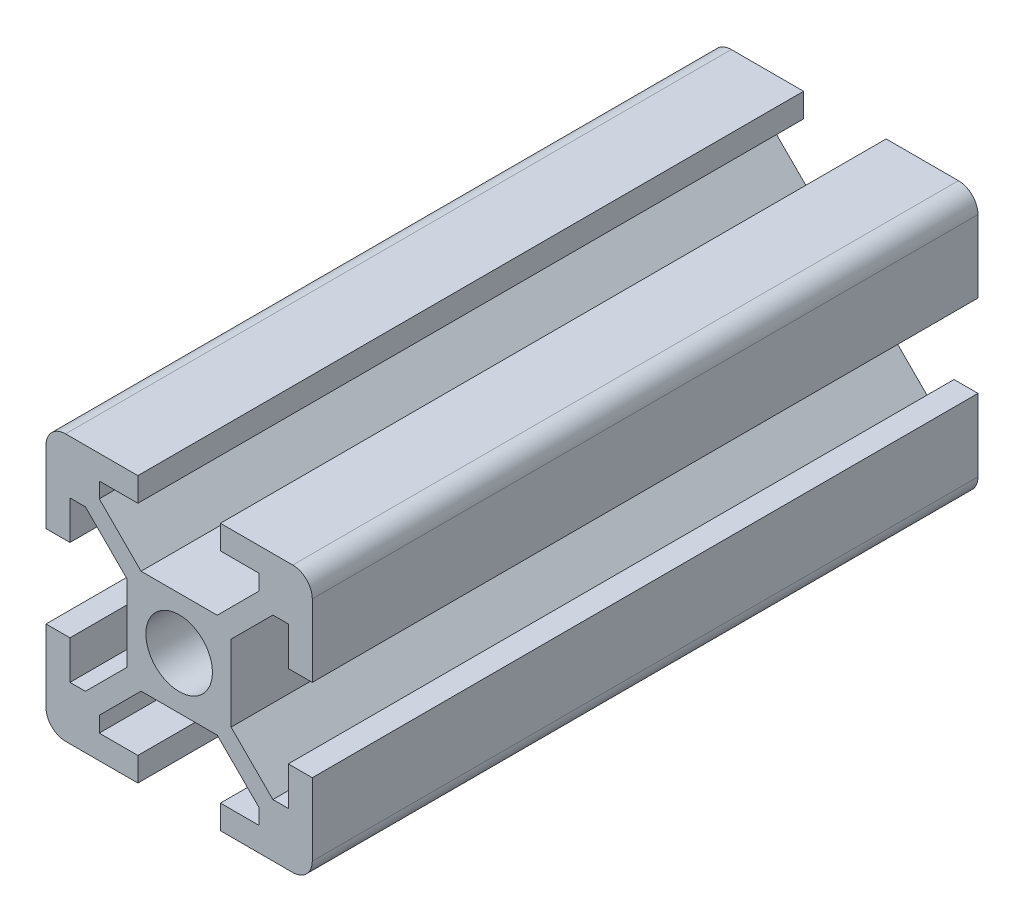
SolidWorks part; units mm, degrees
ref_plane "Front Plane" through (0, 0, 0) normal (0, 0, 1) x (1, 0, 0)
ref_plane "Top Plane" through (0, 0, 0) normal (0, 1, 0) x (1, 0, 0)
ref_plane "Right Plane" through (0, 0, 0) normal (1, 0, 0) x (0, 0, -1)
sketch "Sketch1" plane through (0, 0, 0) normal (0, 0, 1) x (1, 0, 0)
  line L0 (2.8606, 3.9) -> (6, 7.0394)
  line L5 (0, 3.9) -> (2.8606, 3.9)
  line L8 (3.9, 2.8606) -> (3.9, 0)
  line L9 (3.9, 0) -> (3.9, -2.8606)
  line L10 (3.9, -2.8606) -> (7.0394, -6)
  line L11 (6, 7.0394) -> (6, 8.2)
  line L12 (6, 8.2) -> (3.1, 8.2)
  line L13 (3.1, 8.2) -> (3.1, 10)
  line L14 (3.1, 10) -> (10, 10)
  line L15 (10, 10) -> (10, 3.1)
  line L16 (10, 3.1) -> (8.2, 3.1)
  line L17 (8.2, 3.1) -> (8.2, 6)
  line L18 (8.2, 6) -> (7.0394, 6)
  line L19 (7.0394, 6) -> (3.9, 2.8606)
  line L22 (7.0394, -6) -> (8.2, -6)
  line L23 (8.2, -6) -> (8.2, -3.1)
  line L24 (8.2, -3.1) -> (10, -3.1)
  line L25 (10, -3.1) -> (10, -10)
  line L26 (10, -10) -> (3.1, -10)
  line L27 (3.1, -10) -> (3.1, -8.2)
  line L28 (3.1, -8.2) -> (6, -8.2)
  line L29 (6, -8.2) -> (6, -7.0394)
  line L30 (6, -7.0394) -> (2.8606, -3.9)
  line L31 (2.8606, -3.9) -> (0, -3.9)
  line L32 (0, -3.9) -> (-2.8606, -3.9)
  line L33 (-2.8606, -3.9) -> (-6, -7.0394)
  line L34 (-6, -7.0394) -> (-6, -8.2)
  line L35 (-6, -8.2) -> (-3.1, -8.2)
  line L36 (-3.1, -8.2) -> (-3.1, -10)
  line L37 (-3.1, -10) -> (-10, -10)
  line L38 (-10, -10) -> (-10, -3.1)
  line L39 (-10, -3.1) -> (-8.2, -3.1)
  line L40 (-8.2, -3.1) -> (-8.2, -6)
  line L41 (-8.2, -6) -> (-7.0394, -6)
  line L42 (-7.0394, -6) -> (-3.9, -2.8606)
  line L43 (-3.9, -2.8606) -> (-3.9, 0)
  line L44 (-3.9, 0) -> (-3.9, 2.8606)
  line L45 (-3.9, 2.8606) -> (-7.0394, 6)
  line L46 (-7.0394, 6) -> (-8.2, 6)
  line L47 (-8.2, 6) -> (-8.2, 3.1)
  line L48 (-8.2, 3.1) -> (-10, 3.1)
  line L49 (-10, 3.1) -> (-10, 10)
  line L50 (-10, 10) -> (-3.1, 10)
  line L51 (-3.1, 10) -> (-3.1, 8.2)
  line L52 (-3.1, 8.2) -> (-6, 8.2)
  line L53 (-6, 8.2) -> (-6, 7.0394)
  line L54 (-6, 7.0394) -> (-2.8606, 3.9)
  line L55 (-2.8606, 3.9) -> (0, 3.9)
  circle A0 centre (0, 0) radius 2.5
  point P0 (0, 0)
  dimension "D9" = 5
  dimension "D1" = 45
  dimension "D2" = 10
  dimension "D3" = 6.1
  dimension "D4" = 3.1
  dimension "D5" = 1.47
  dimension "D6" = 4.3
  dimension "D7" = 6
  dimension "D8" = 4
extrude "Boss-Extrude1" add sketch "Sketch1" along normal blind 50
fillet "Fillet1" radius 1.47 4 edges at (-10, -10, 25) (-10, 10, 25) (10, -10, 25) (10, 10, 25)
sketch "Sketch2" plane through (0, -3.9, 0) normal (0, -1, 0) x (1, 0, 0)
  line L0 (-2.8606, 50) -> (2.8606, 50) construction
  circle A0 centre (0, 40) radius 1.5
  dimension "D1" = 3
  dimension "D2" = 10
extrude "Cut-Extrude1" cut sketch "Sketch2" against normal through all
sketch "Sketch3" plane through (0, 3.9, 0) normal (0, 1, 0) x (1, 0, 0)
  line L0 (2.8606, 0) -> (-2.8606, 0) construction
  circle A0 centre (0, -10) radius 1.5
  dimension "D1" = 3
  dimension "D2" = 10
extrude "Cut-Extrude2" cut sketch "Sketch3" against normal through all
